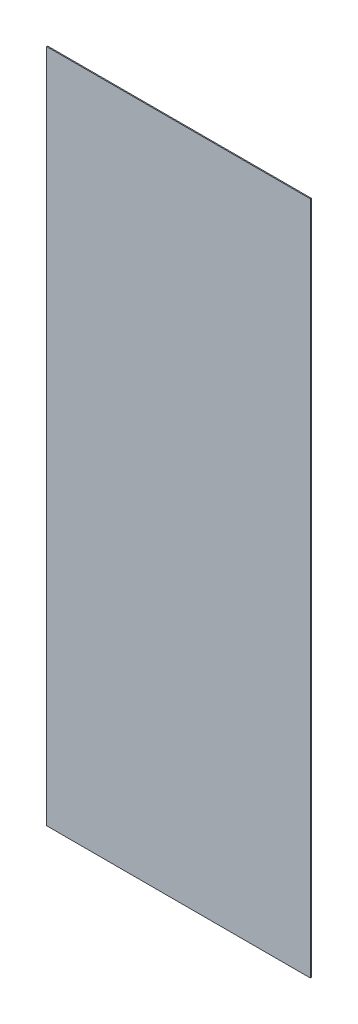
SolidWorks part; units mm, degrees
ref_plane "Alzado" through (0, 0, 0) normal (0, 0, 1) x (1, 0, 0)
ref_plane "Planta" through (0, 0, 0) normal (0, 1, 0) x (1, 0, 0)
ref_plane "Vista lateral" through (0, 0, 0) normal (1, 0, 0) x (0, 0, -1)
sketch "Croquis1" plane through (0, 0, 0) normal (0, 0, 1) x (1, 0, 0)
  line L1 (-250, 640) -> (250, 640)
  line L2 (-250, 640) -> (-250, -640)
  line L3 (-250, -640) -> (250, -640)
  line L4 (250, 640) -> (250, -640)
  line L5 (-250, 640) -> (250, -640) construction
  line L6 (-250, -640) -> (250, 640) construction
  point P0 (0, 0)
  dimension "D1" = 500
  dimension "D2" = 1280
extrude "Saliente-Extruir1" add sketch "Croquis1" along normal blind 1.9
